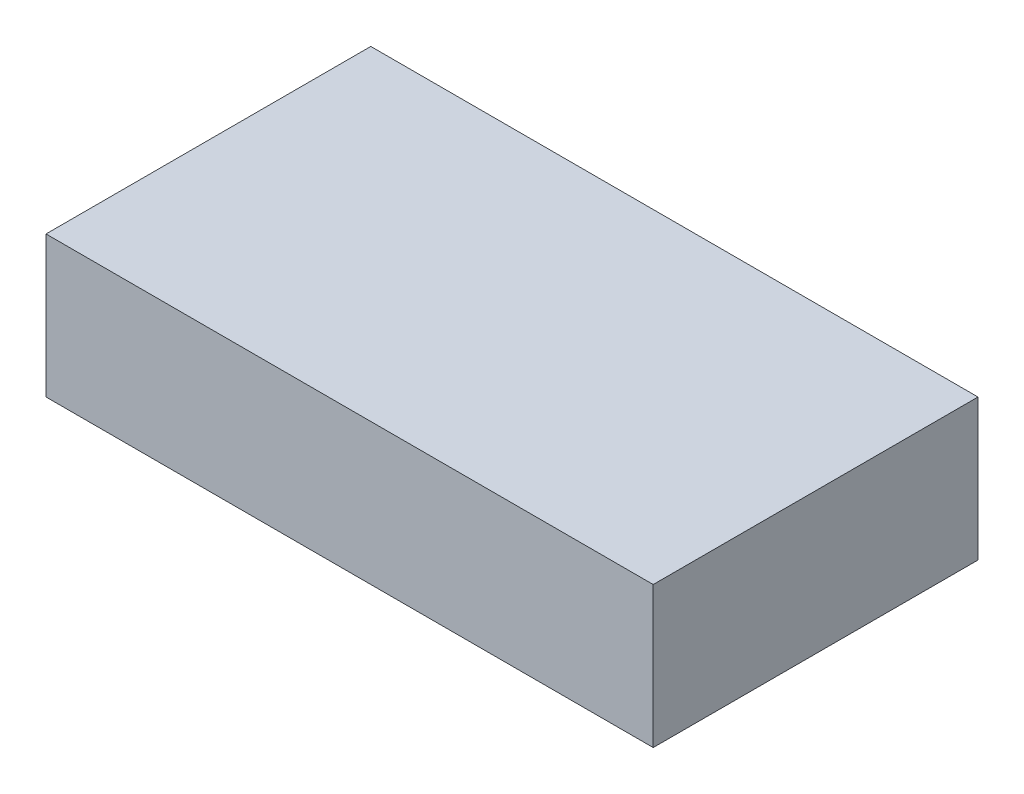
SolidWorks part; units mm, degrees
ref_plane "Front Plane" through (0, 0, 0) normal (0, 0, 1) x (1, 0, 0)
ref_plane "Top Plane" through (0, 0, 0) normal (0, 1, 0) x (1, 0, 0)
ref_plane "Right Plane" through (0, 0, 0) normal (1, 0, 0) x (0, 0, -1)
sketch "Sketch1" plane through (0, 0, 0) normal (0, 1, 0) x (1, 0, 0)
  line L1 (-107.5, -57.5) -> (107.5, -57.5)
  line L2 (-107.5, -57.5) -> (-107.5, 57.5)
  line L3 (-107.5, 57.5) -> (107.5, 57.5)
  line L4 (107.5, -57.5) -> (107.5, 57.5)
  line L5 (-107.5, -57.5) -> (107.5, 57.5) construction
  line L6 (-107.5, 57.5) -> (107.5, -57.5) construction
  point P0 (0, 0)
  dimension "D1" = 215
  dimension "D2" = 115
extrude "Boss-Extrude1" add sketch "Sketch1" along normal blind 50
